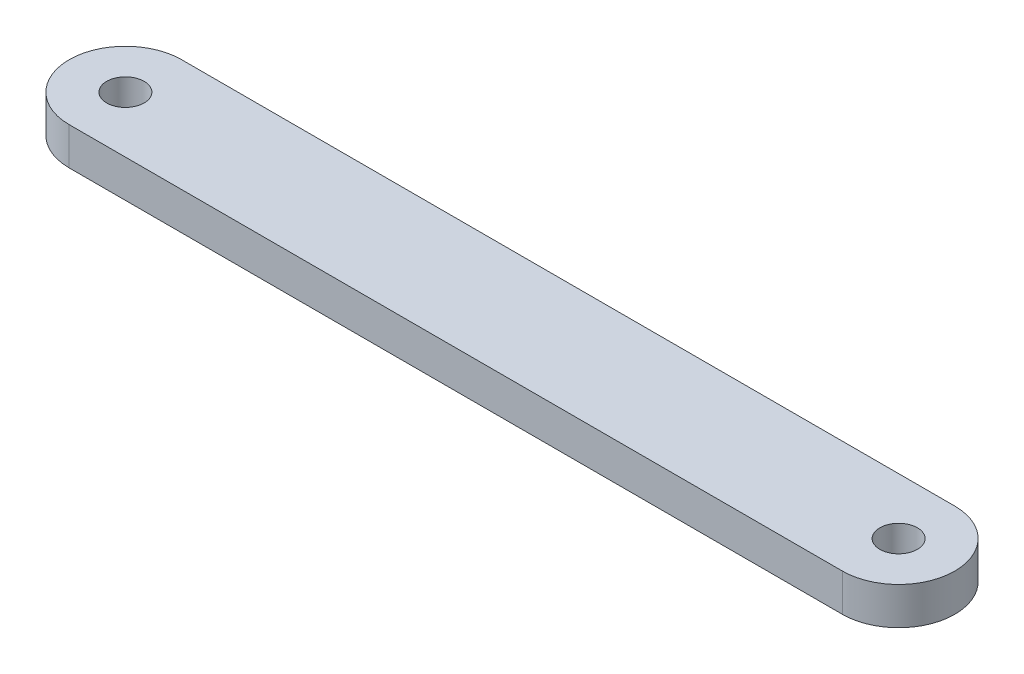
SolidWorks part; units mm, degrees
ref_plane "Front Plane" through (0, 0, 0) normal (0, 0, 1) x (1, 0, 0)
ref_plane "Top Plane" through (0, 0, 0) normal (0, 1, 0) x (1, 0, 0)
ref_plane "Right Plane" through (0, 0, 0) normal (1, 0, 0) x (0, 0, -1)
sketch "Sketch1" plane through (0, 0, 0) normal (0, 1, 0) x (1, 0, 0)
  line L0 (-51.5566, 0) -> (51.5566, 0) construction
  line L1 (-51.5566, 7.5) -> (51.5566, 7.5)
  line L2 (-51.5566, -7.5) -> (51.5566, -7.5)
  arc A0 (-51.5566, 7.5) -> (-51.5566, -7.5) centre (-51.5566, 0) ccw
  arc A1 (51.5566, -7.5) -> (51.5566, 7.5) centre (51.5566, 0) ccw
  circle A2 centre (-51.5566, 0) radius 2.4
  circle A3 centre (51.5566, 0) radius 2.4
  point P3 (0, 0)
  dimension "D1" = 103.1132
  dimension "D2" = 15
extrude "Boss-Extrude1" add sketch "Sketch1" along normal blind 5
scale "Scale1" scale about centroid uniform scaling yes scale factor 0.8
sketch "Sketch2" plane through (0, 4.5, 0) normal (0, 1, 0) x (1, 0, 0)
  circle A0 centre (-41.2453, 0) radius 2
  circle A1 centre (41.2453, 0) radius 2
extrude "Cut-Extrude1" cut sketch "Sketch2" against normal through all
